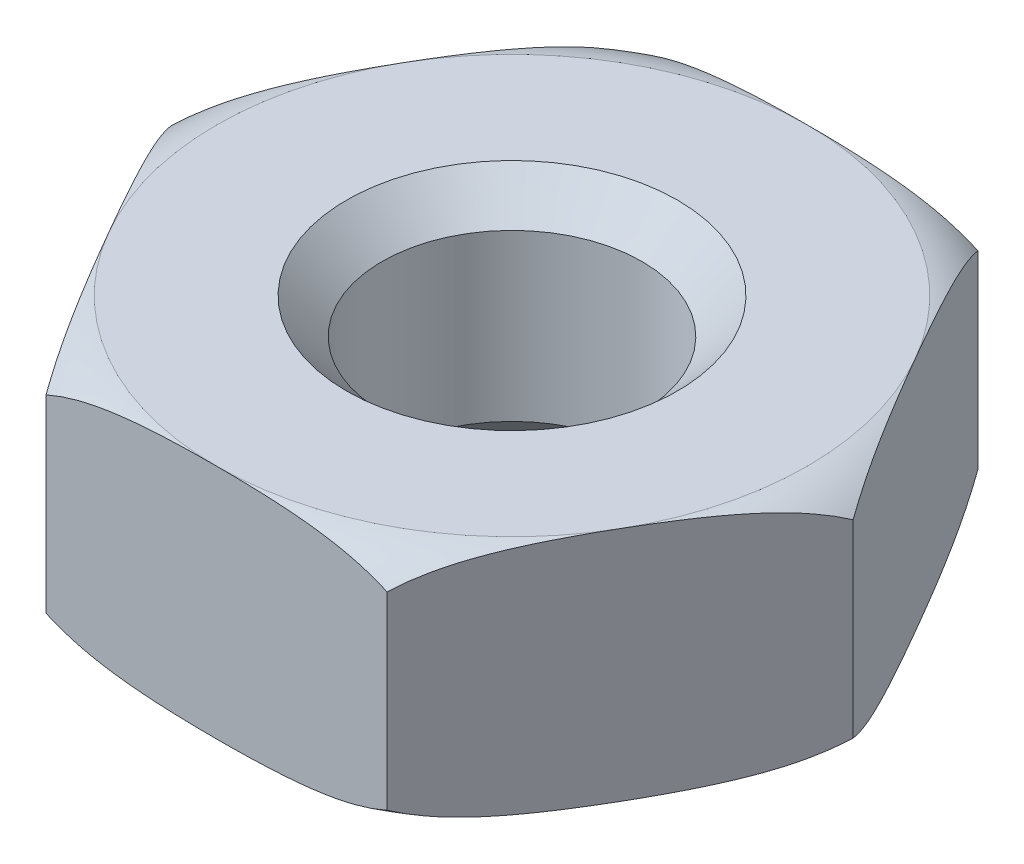
SolidWorks part; units mm, degrees
ref_plane "Front Plane" through (0, 0, 0) normal (0, 0, 1) x (1, 0, 0)
ref_plane "Top Plane" through (0, 0, 0) normal (0, 1, 0) x (1, 0, 0)
ref_plane "Right Plane" through (0, 0, 0) normal (1, 0, 0) x (0, 0, -1)
sketch "Sketch1" plane through (0, 0, 0) normal (0, 1, 0) x (1, 0, 0)
  line L1 (2.8868, 0) -> (1.4434, 2.5)
  line L2 (1.4434, 2.5) -> (-1.4434, 2.5)
  line L3 (-1.4434, 2.5) -> (-2.8868, 0)
  line L4 (-2.8868, 0) -> (-1.4434, -2.5)
  line L5 (-1.4434, -2.5) -> (1.4434, -2.5)
  line L6 (1.4434, -2.5) -> (2.8868, 0)
  circle A0 centre (0, 0) radius 2.5 construction
  circle A1 centre (0, 0) radius 1.1
  dimension "D1" = 2.2
  dimension "D2" = 5
extrude "Boss-Extrude1" add sketch "Sketch1" along normal mid plane 2
sketch "Sketch2" plane through (0, 0, 0) normal (0, 0, 1) x (1, 0, 0)
  line L0 (-2.8868, 0.8007) -> (-2.8868, 1)
  line L1 (-2.8868, 1) -> (-2.8868, -1) construction
  line L7 (0, 0) -> (0, 1) construction
  line L8 (1.4434, 1) -> (2.8868, 1) construction
  line L9 (1.1, 1) -> (-1.1, 1) construction
  line L10 (-2.8868, 1) -> (-2.5, 1)
  line L11 (-1.4, 1) -> (-1.1, 1)
  line L12 (-1.4434, 1) -> (1.4434, 1) construction
  line L13 (-1.1, 1) -> (-1.1, 0.7)
  line L14 (-1.1, 0.7) -> (-1.4, 1)
  line L15 (-2.8868, 1) -> (-1.4434, 1) construction
  line L16 (0, 0) -> (-2.8868, 0) construction
  line L17 (-2.8868, -0.8007) -> (-2.8868, -1)
  line L18 (-2.8868, -1) -> (-2.5, -1)
  arc A1 (-2.5, 1) -> (-2.8868, 0.8007) centre (-2.3187, 0.1734) ccw
  arc A2 (-2.5, -1) -> (-2.8868, -0.8007) centre (-2.3187, -0.1734) cw
  dimension "D2" = 2.5
  dimension "D1" = 1.4
revolve "Cut-Revolve1" cut sketch "Sketch2" angle 360 about L7
mirror "Mirror1" about plane through (0, 0, 0) normal (0, 1, 0) of "Cut-Revolve1"
